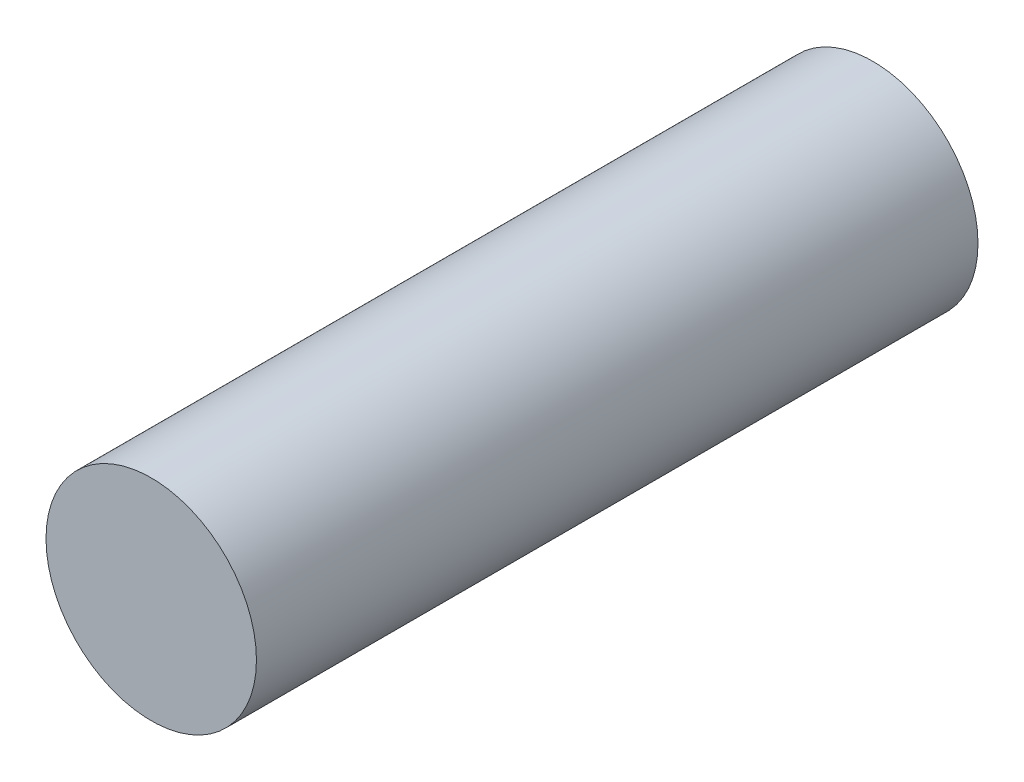
SolidWorks part; units mm, degrees
ref_plane "Front" through (0, 0, 0) normal (0, 0, 1) x (1, 0, 0)
ref_plane "Top" through (0, 0, 0) normal (0, 1, 0) x (1, 0, 0)
ref_plane "Right" through (0, 0, 0) normal (1, 0, 0) x (0, 0, -1)
sketch "Sketch1" plane through (0, 0, 0) normal (0, 0, 1) x (1, 0, 0)
  circle A0 centre (0, 0) radius 17.5
  dimension "D1" = 35
extrude "Boss-Extrude1" add sketch "Sketch1" along normal blind 120
